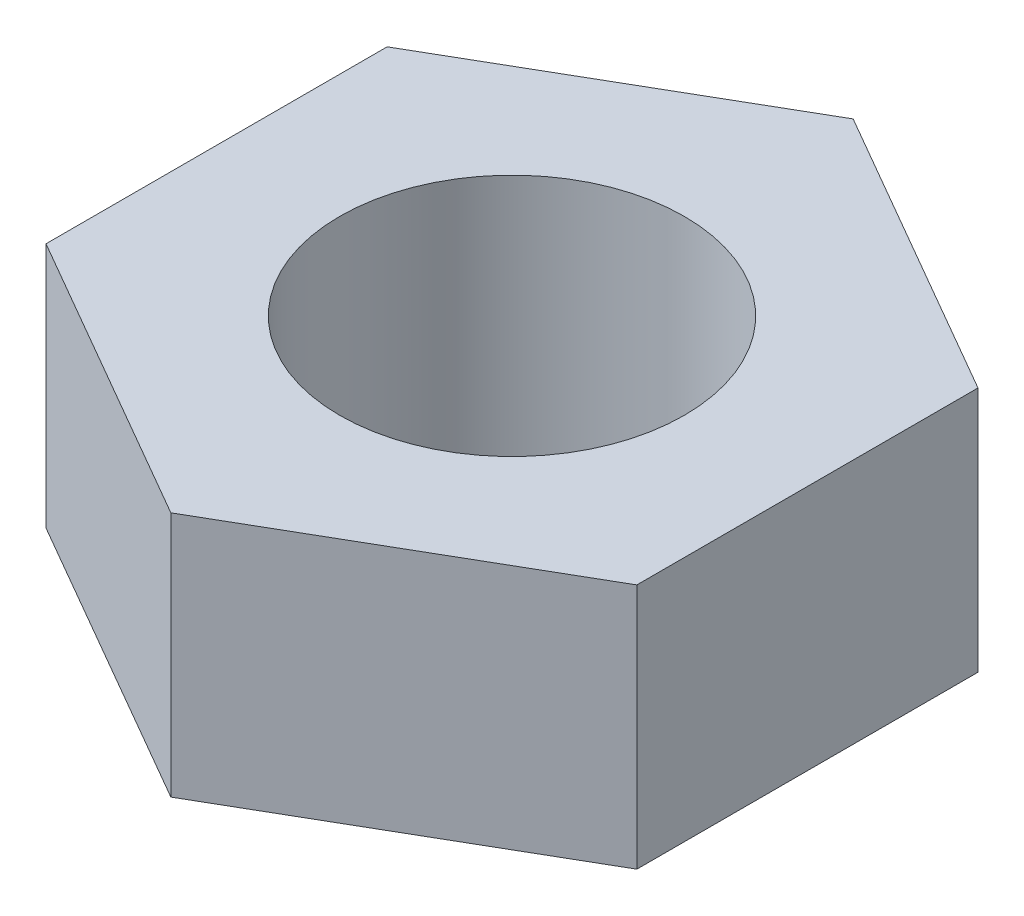
SolidWorks part; units mm, degrees
ref_plane "Front Plane" through (0, 0, 0) normal (0, 0, 1) x (1, 0, 0)
ref_plane "Top Plane" through (0, 0, 0) normal (0, 1, 0) x (1, 0, 0)
ref_plane "Right Plane" through (0, 0, 0) normal (1, 0, 0) x (0, 0, -1)
sketch "Sketch2" plane through (0, 0, 0) normal (0, 1, 0) x (1, 0, 0)
  line L1 (12, -6.9282) -> (12, 6.9282)
  line L2 (12, 6.9282) -> (0, 13.8564)
  line L3 (0, 13.8564) -> (-12, 6.9282)
  line L4 (-12, 6.9282) -> (-12, -6.9282)
  line L5 (-12, -6.9282) -> (0, -13.8564)
  line L6 (0, -13.8564) -> (12, -6.9282)
  circle A0 centre (0, 0) radius 12 construction
  circle A1 centre (0, 0) radius 7
  dimension "D2" = 14
  dimension "D1" = 24
extrude "Boss-Extrude1" add sketch "Sketch2" along normal blind 10
